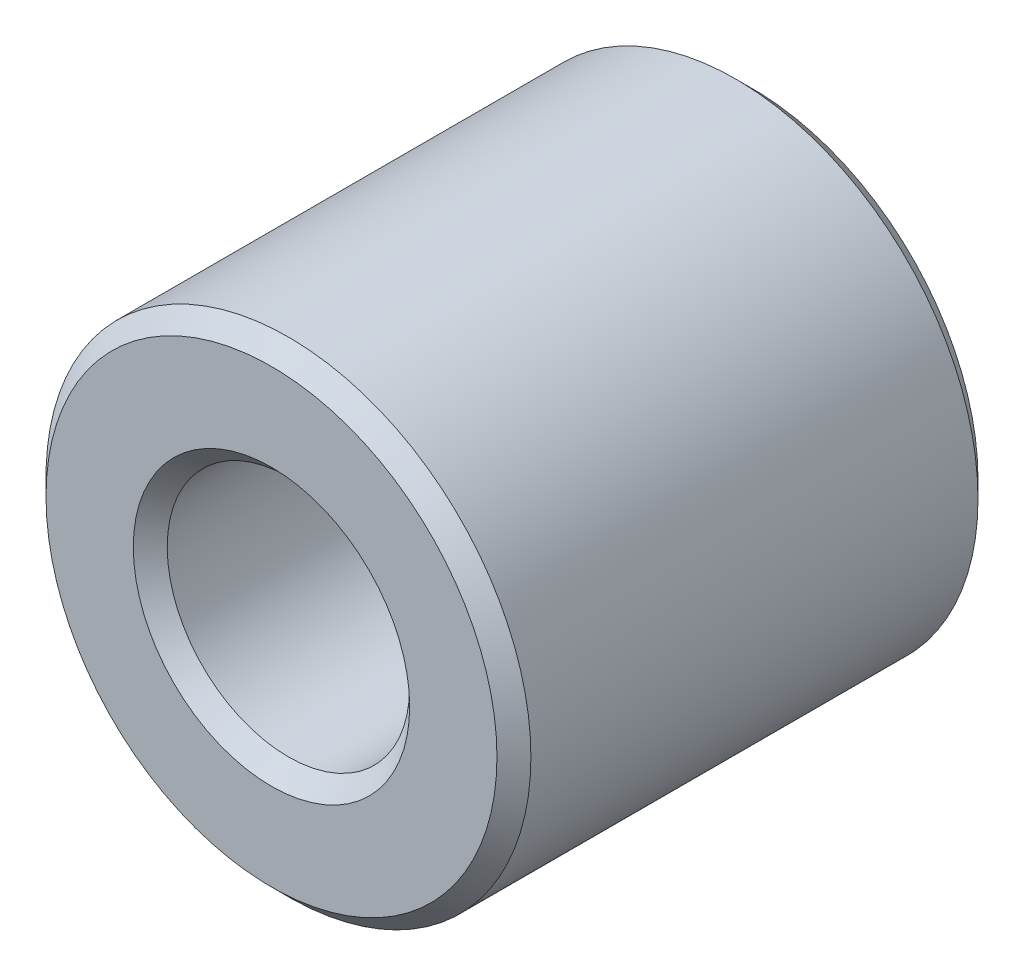
SolidWorks part; units mm, degrees
ref_plane "Front Plane" through (0, 0, 0) normal (0, 0, 1) x (1, 0, 0)
ref_plane "Top Plane" through (0, 0, 0) normal (0, 1, 0) x (1, 0, 0)
ref_plane "Right Plane" through (0, 0, 0) normal (1, 0, 0) x (0, 0, -1)
sketch "Sketch1" plane through (0, 0, 0) normal (0, 0, 1) x (1, 0, 0)
  line L0 (1.6002, 0) -> (3.2004, 0) construction
  circle A0 centre (0, 0) radius 1.6002 construction
  circle A1 centre (0, 0) radius 3.2004 construction
  circle A2 centre (0, 0) radius 3.175 construction
  circle A3 centre (0, 0) radius 1.5875 construction
  dimension "For Shaft Diameter" = 3.175
  dimension "For Housing ID" = 6.35
  dimension "OD" = 6.4008
  dimension "ID" = 3.2004
  dimension "D3" = 1.6002
sketch "Sketch13" plane through (0, 0, 0) normal (1, 0, 0) x (0, 0, -1)
  line L0 (3.175, 0) -> (-3.175, 0) construction
  line L1 (3.175, 3.2004) -> (-3.175, 3.2004) construction
  line L2 (0, 3.2004) -> (0, -3.2004) construction
  line L3 (0, 3.2004) -> (0, -3.2004) construction
  point P4 (0, 0)
  point P8 (0, 3.2004)
  dimension "Length" = 6.35
sketch "Sketch14" plane through (0, 0, 0) normal (0, 0, 1) x (1, 0, 0)
  circle A0 centre (0, 0) radius 1.6002 construction
  circle A1 centre (0, 0) radius 3.2004 construction
  circle A2 centre (0, 0) radius 1.6002
  circle A3 centre (0, 0) radius 3.2004
extrude "Boss-Extrude1" add sketch "Sketch14" against normal up to vertex (3.175 mm away) and the other way up to vertex (3.175 mm away) up to point (0, 3.2004, -3.175) other way up to point (0, 3.2004, 3.175)
chamfer "Chamfer1" distance 0.224 angle 45 4 edges at (3.2004, 0, -3.175) (1.6002, 0, -3.175) (1.6002, 0, 3.175) (3.2004, 0, 3.175)
equation "\"D1@Chamfer1\"=(\"OD@Sketch1\"-\"ID@Sketch1\")*.07"
